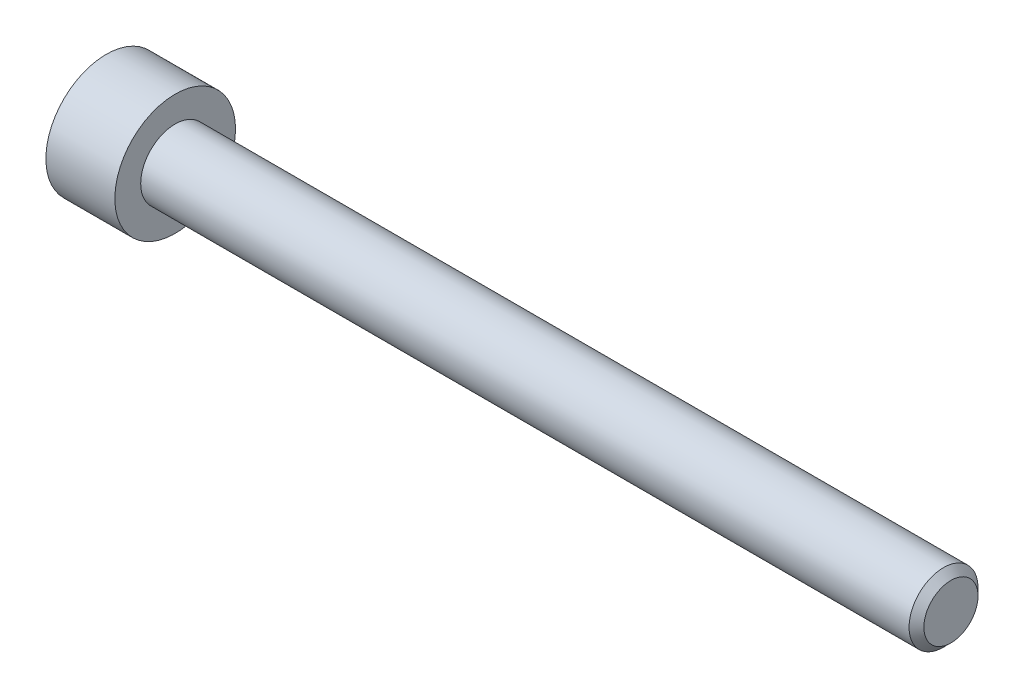
SolidWorks part; units mm, degrees
ref_plane "Front Plane" through (0, 0, 0) normal (0, 0, 1) x (1, 0, 0)
ref_plane "Top Plane" through (0, 0, 0) normal (0, 1, 0) x (1, 0, 0)
ref_plane "Right Plane" through (0, 0, 0) normal (1, 0, 0) x (0, 0, -1)
sketch "Sketch1" plane through (0, 0, 0) normal (0, 0, 1) x (1, 0, 0)
  line L0 (-4, 3.5) -> (-4, 0)
  line L1 (-4, 0) -> (0, 0)
  line L2 (0, 0) -> (0, 3.5)
  line L3 (0, 3.5) -> (-4, 3.5)
  line L4 (-4, 0) -> (0, 0) construction
revolve "Revolve1" add sketch "Sketch1" angle 360 about L4
sketch "Sketch2" plane through (0, 0, 0) normal (1, 0, 0) x (0, 0, -1)
  circle A0 centre (0, 0) radius 2
extrude "Boss-Extrude1" add sketch "Sketch2" along normal blind 45
sketch "Sketch3" plane through (-4, 0, 0) normal (-1, 0, 0) x (0, 0, 1)
  line L0 (1.5, -0.866) -> (1.5, 0.866)
  line L1 (1.5, 0.866) -> (0, 1.7321)
  line L2 (0, 1.7321) -> (-1.5, 0.866)
  line L3 (-1.5, 0.866) -> (-1.5, -0.866)
  line L4 (-1.5, -0.866) -> (0, -1.7321)
  line L5 (0, -1.7321) -> (1.5, -0.866)
extrude "Cut-Extrude1" cut sketch "Sketch3" against normal blind 2
sketch "Sketch4" plane through (0, 0, 0) normal (0, 0, 1) x (1, 0, 0)
  line L0 (-2, 1.5) -> (-2, 0)
  line L1 (-2, 0) -> (-1.5981, 0)
  line L2 (-1.5981, 0) -> (-2, 1.5)
  line L3 (-2, 0) -> (-1.598, 0) construction
revolve "Cut-Revolve1" cut sketch "Sketch4" angle 360 about L3
chamfer "Chamfer1" distance 0.4295 angle 45 1 edges at (45, 0, -2)
